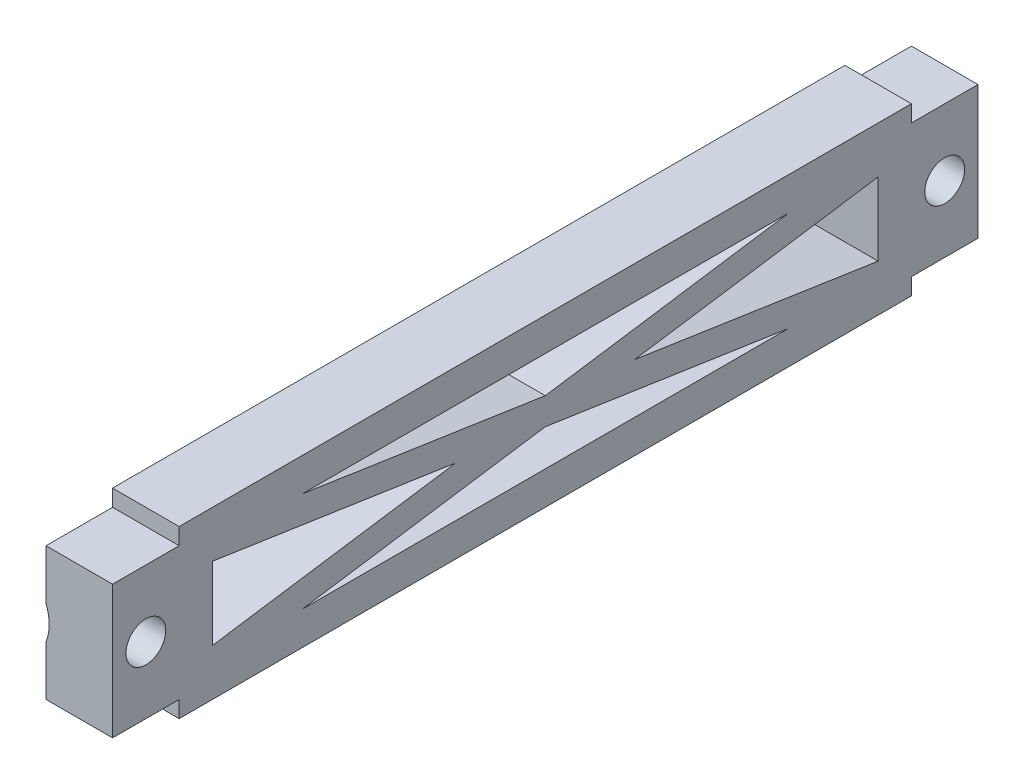
SolidWorks part; units mm, degrees
material "6061-T6 (SS)"
ref_plane "Front" through (0, 0, 0) normal (0, 0, 1) x (1, 0, 0)
ref_plane "Top" through (0, 0, 0) normal (0, 1, 0) x (1, 0, 0)
ref_plane "Right" through (0, 0, 0) normal (1, 0, 0) x (0, 0, -1)
sketch "Sketch1" plane through (0, 0, 0) normal (1, 0, 0) x (0, 0, -1)
  line L0 (41.275, 15.875) -> (41.275, 0) construction
  line L1 (0, 0) -> (82.55, 0)
  line L2 (0, 0) -> (0, 15.875)
  line L3 (0, 15.875) -> (82.55, 15.875)
  line L4 (82.55, 0) -> (82.55, 15.875)
  line L5 (82.55, 14.2875) -> (76.2, 14.2875)
  line L6 (82.55, 14.2875) -> (82.55, 1.5875)
  line L7 (82.55, 1.5875) -> (76.2, 1.5875)
  line L8 (76.2, 1.5875) -> (76.2, 0)
  line L9 (0, 1.5875) -> (6.35, 1.5875)
  line L10 (76.2, 14.2875) -> (76.2, 15.875)
  line L11 (0, 14.2875) -> (6.35, 14.2875)
  line L12 (6.35, 14.2875) -> (6.35, 15.875)
  line L13 (6.35, 1.5875) -> (6.35, 0)
  dimension "D1" = 15.875
  dimension "D2" = 82.55
  dimension "D3" = 6.35
  dimension "D4" = 1.5875
  dimension "D5" = 1.5875
extrude "Boss-Extrude1" add sketch "Sketch1" along normal blind 6.35 contours L3 L0 L1 L8 L7 L4 L5 L10 | L0 L3 L12 L11 L2 L9 L13 L1
hole_wizard "CSK for #6 Flat Head Machine Screw (100)1" positions "Sketch3" profile "Sketch2" countersink size "#6" standard "ANSI Inch" end condition through all
sketch "Sketch3" plane through (0, 0, 0) normal (-1, 0, 0) x (0, 0, 1)
  line L1 (-82.55, 14.2875) -> (-76.2, 14.2875) construction
  line L2 (0, 14.2875) -> (-6.35, 14.2875) construction
  line L3 (-6.35, 15.875) -> (-76.2, 15.875) construction
  point P0 (-79.375, 7.9375)
  point P2 (-79.375, 7.9375)
  point P4 (-3.175, 7.9375)
  point P6 (-3.175, 7.9375)
  point P13 (-79.375, 14.2875)
  point P16 (-3.175, 14.2875)
  dimension "D1" = 7.9375
  dimension "D2" = 7.9375
sketch "Sketch2" plane through (0, 7.9375, -79.375) normal (0, 1, 0) x (0, 0, 1)
  line L0 (0, 0) -> (0, 6.35)
  line L1 (0, 6.35) -> (1.8986, 6.35)
  line L2 (1.8986, 6.35) -> (1.8986, 1.38)
  line L3 (1.8986, 1.38) -> (3.5433, 0)
  line L5 (3.5433, 0) -> (0, 0)
  line L6 (-1.8986, 1.38) -> (-3.5433, 0) construction
  line L11 (0, -6.35) -> (0, 107.95) construction
  dimension "Thru Hole Dia." = 3.7973
  dimension "Thru Hole Depth" = 6.35
  dimension "Near C'Sink Dia." = 7.0866
  dimension "Near C'Sink Angle" = 100
sketch "Sketch4" plane through (0, 0, 0) normal (-1, 0, 0) x (0, 0, 1)
  line L0 (-6.35, 15.875) -> (-76.2, 15.875) construction
  line L1 (-73.025, 12.7) -> (-9.525, 12.7)
  line L2 (-73.025, 12.7) -> (-73.025, 3.175)
  line L3 (-73.025, 3.175) -> (-9.525, 3.175)
  line L4 (-9.525, 12.7) -> (-9.525, 3.175)
  line L5 (-73.025, 12.7) -> (-9.525, 3.175) construction
  line L6 (-73.025, 3.175) -> (-9.525, 12.7) construction
  line L7 (-6.35, 0) -> (-76.2, 0) construction
  line L8 (-73.2134, 11.4441) -> (-9.7134, 1.9191)
  line L9 (-72.8366, 1.9191) -> (-9.3366, 11.4441)
  line L10 (-72.8366, 13.9559) -> (-9.3366, 4.4309)
  line L11 (-73.2134, 4.4309) -> (-9.7134, 13.9559)
  arc A0 (-73.2134, 11.4441) -> (-72.8366, 13.9559) centre (-73.025, 12.7) cw
  arc A1 (-9.7134, 1.9191) -> (-9.3366, 4.4309) centre (-9.525, 3.175) ccw
  arc A2 (-72.8366, 1.9191) -> (-73.2134, 4.4309) centre (-73.025, 3.175) cw
  arc A3 (-9.3366, 11.4441) -> (-9.7134, 13.9559) centre (-9.525, 12.7) ccw
  point P0 (-41.275, 7.9375)
  dimension "D1" = 3.175
  dimension "D2" = 3.175
  dimension "D3" = 3.175
  dimension "D4" = 3.175
  dimension "D5" = 1.27
  dimension "D6" = 1.27
extrude "Cut-Extrude1" cut sketch "Sketch4" against normal through all contours L2 L11 L8 | L10 L11 L1 | L9 L10 L4 | L9 L3 L8
